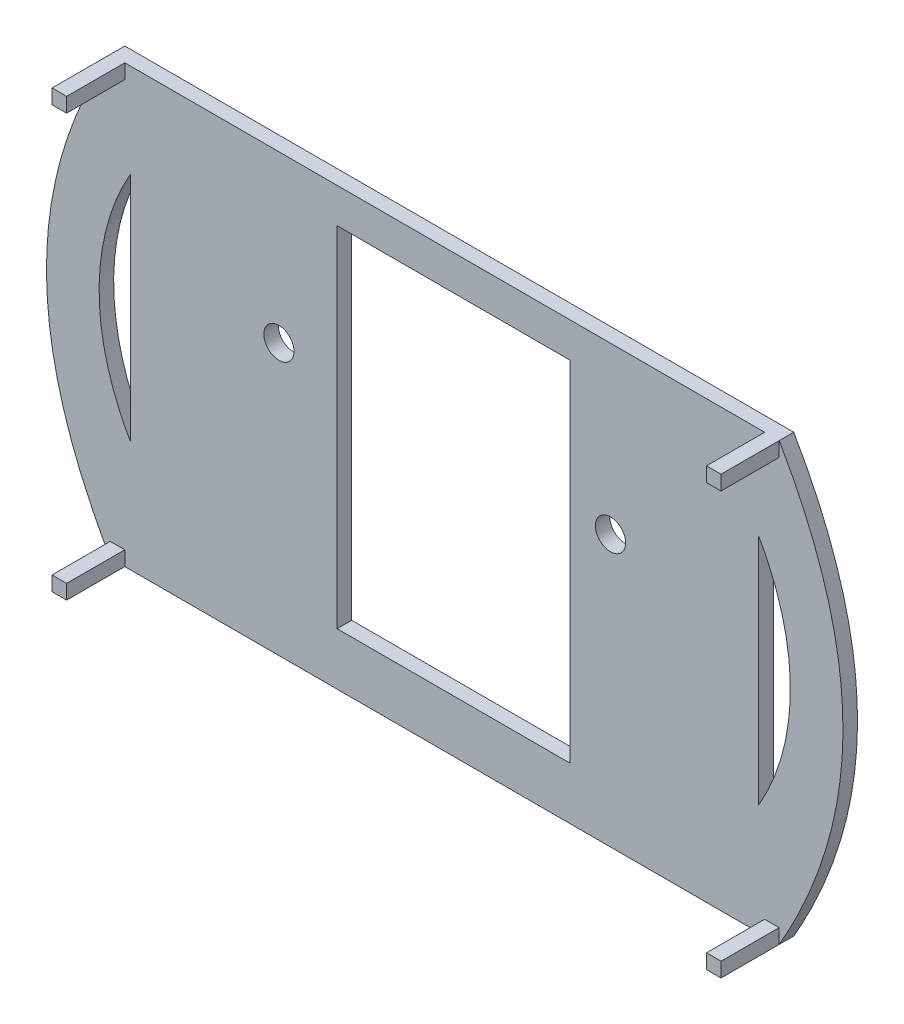
SolidWorks part; units mm, degrees
ref_plane "Front Plane" through (0, 0, 0) normal (0, 0, 1) x (1, 0, 0)
ref_plane "Top Plane" through (0, 0, 0) normal (0, 1, 0) x (1, 0, 0)
ref_plane "Right Plane" through (0, 0, 0) normal (1, 0, 0) x (0, 0, -1)
sketch "Sketch1" plane through (0, 0, 0) normal (0, 0, 1) x (1, 0, 0)
  line L0 (19.4754, 36.1268) -> (19.4754, -59.1232) construction
  line L1 (-53.5496, 36.1268) -> (92.5004, 36.1268)
  line L2 (-53.5496, 36.1268) -> (-53.5496, -59.1232)
  line L3 (-53.5496, -59.1232) -> (92.5004, -59.1232)
  line L4 (92.5004, 36.1268) -> (92.5004, -59.1232)
  spline S0 degree 3 poles (-53.5496, 36.1268) (-70.0597, 7.5305) (-74.0467, -23.6212) (-53.5496, -59.1232) knots 0 0 0 0 1 1 1 1
  spline S1 degree 3 poles (92.5004, 36.1268) (109.0104, 7.5305) (112.9975, -23.6212) (92.5004, -59.1232) knots 0 0 0 0 1 1 1 1
  dimension "D1" = 146.05
  dimension "D2" = 95.25
extrude "Boss-Extrude1" add sketch "Sketch1" along normal blind 3.175 contours L2 S0 | L0 L1 L2 L3 | L1 L0 L3 L4 | S1 L4
sketch "Sketch2" plane through (0, 0, 3.175) normal (0, 0, 1) x (1, 0, 0)
  line L0 (-53.5496, -59.1232) -> (92.5004, -59.1232) construction
  line L1 (-4.0196, 28.5068) -> (46.7804, 28.5068)
  line L2 (-4.0196, 28.5068) -> (-4.0196, -47.6932)
  line L3 (-4.0196, -47.6932) -> (46.7804, -47.6932)
  line L4 (46.7804, 28.5068) -> (46.7804, -47.6932)
  line L5 (-53.5496, 36.1268) -> (92.5004, 36.1268) construction
  line L6 (19.4754, 36.1268) -> (19.4754, -59.1232) construction
  line L7 (-49.077, 15.8068) -> (-49.077, -34.9932)
  line L8 (88.0278, 15.8068) -> (88.0278, -34.9932)
  circle A0 centre (-16.7196, 0) radius 3.302
  circle A1 centre (55.6704, 0) radius 3.302
  spline S0 degree 3 poles (-49.077, 15.8068) (-57.59, 1.0619) (-58.9552, -17.8837) (-49.077, -34.9932) knots 0 0 0 0 1 1 1 1
  spline S1 degree 3 poles (88.0278, 15.8068) (96.5408, 1.0619) (97.906, -17.8837) (88.0278, -34.9932) knots 0 0 0 0 1 1 1 1
  dimension "D7" = 6.604
  dimension "D9" = 50.8
  dimension "D1" = 50.8
  dimension "D2" = 76.2
  dimension "D3" = 11.43
  dimension "D4" = 7.62
  dimension "D5" = 49.53
  dimension "D6" = 45.72
  dimension "D8" = 12.7
  dimension "D10" = 24.13
extrude "Cut-Extrude1" cut sketch "Sketch2" against normal blind 3.81
sketch "Sketch3" plane through (0, 0, 3.175) normal (0, 0, 1) x (1, 0, 0)
  line L0 (19.4754, 36.1268) -> (19.4754, -59.1232) construction
  line L1 (-53.5496, 36.1268) -> (-50.3746, 36.1268)
  line L2 (-53.5496, 36.1268) -> (-53.5496, 32.9518)
  line L3 (-53.5496, 32.9518) -> (-50.3746, 32.9518)
  line L4 (-50.3746, 36.1268) -> (-50.3746, 32.9518)
  line L5 (-53.5496, -55.9482) -> (-50.3746, -55.9482)
  line L6 (-53.5496, -55.9482) -> (-53.5496, -59.1232)
  line L7 (-53.5496, -59.1232) -> (-50.3746, -59.1232)
  line L8 (-50.3746, -55.9482) -> (-50.3746, -59.1232)
  line L9 (-53.5496, 36.1268) -> (92.5004, 36.1268) construction
  line L10 (-53.5496, -59.1232) -> (92.5004, -59.1232) construction
  line L11 (89.3254, -55.9482) -> (89.3254, -59.1232)
  line L12 (92.5004, -59.1232) -> (89.3254, -59.1232)
  line L13 (92.5004, -55.9482) -> (92.5004, -59.1232)
  line L14 (92.5004, -55.9482) -> (89.3254, -55.9482)
  line L15 (89.3254, 36.1268) -> (89.3254, 32.9518)
  line L16 (92.5004, 32.9518) -> (89.3254, 32.9518)
  line L17 (92.5004, 36.1268) -> (92.5004, 32.9518)
  line L18 (92.5004, 36.1268) -> (89.3254, 36.1268)
  dimension "D1" = 3.175
  dimension "D2" = 3.175
  dimension "D3" = 3.175
  dimension "D4" = 3.175
  dimension "D5" = 0
  dimension "D6" = 0
extrude "Boss-Extrude2" add sketch "Sketch3" along normal blind 12.7
